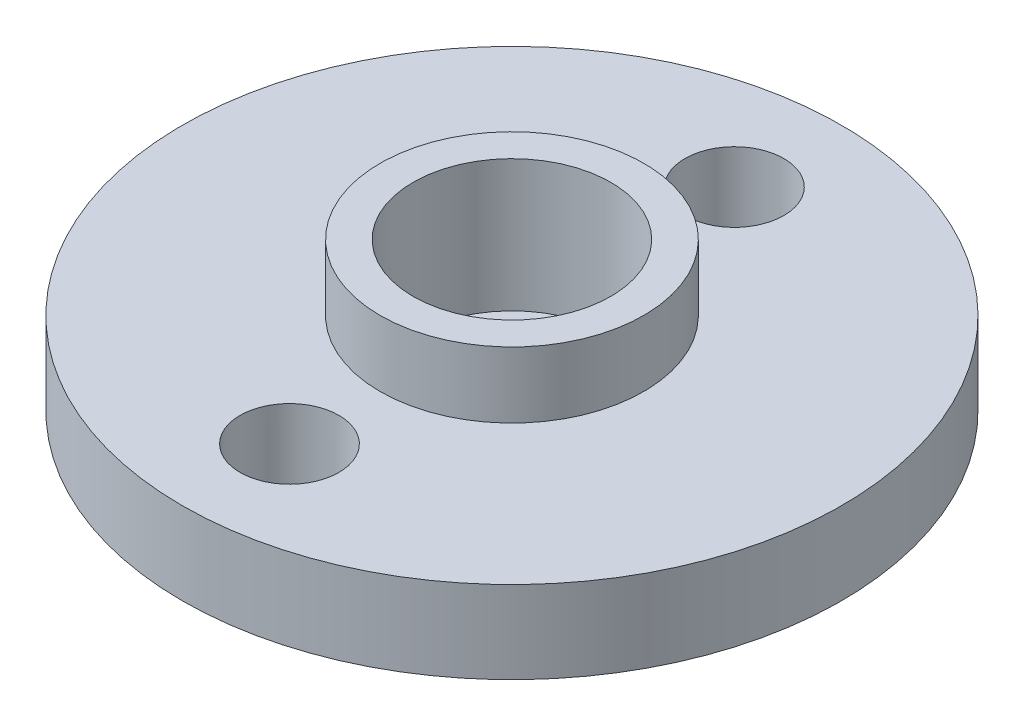
SolidWorks part; units mm, degrees
material "Chrome Stainless Steel"
ref_plane "Front Plane" through (0, 0, 0) normal (0, 0, 1) x (1, 0, 0)
ref_plane "Top Plane" through (0, 0, 0) normal (0, 1, 0) x (1, 0, 0)
ref_plane "Right Plane" through (0, 0, 0) normal (1, 0, 0) x (0, 0, -1)
sketch "Sketch1" plane through (0, 0, 0) normal (0, 0, 1) x (1, 0, 0)
  line L0 (0, 3.4245) -> (0, 0) construction
  line L1 (3, 0) -> (4, 0)
  line L2 (4, 0) -> (4, -2)
  line L3 (4, -2) -> (10, -2)
  line L4 (10, -2) -> (10, -4.5)
  line L5 (10, -4.5) -> (1.5, -4.5)
  line L6 (0, -4.5) -> (0, 0) construction
  line L7 (3, 0) -> (3, -4)
  line L8 (3, -4) -> (1.5, -4)
  line L9 (1.5, -4) -> (1.5, -4.5)
  line L10 (1.5, -4.5) -> (0, -4.5) construction
  line L11 (0, 0) -> (0, -4.5) construction
  line L12 (0, -4.5) -> (0, -6.9835) construction
  line L13 (0, 0) -> (3, 0) construction
  dimension "D1" = 10
  dimension "D2" = 4
  dimension "D3" = 3
  dimension "D4" = 2
  dimension "D5" = 2.5
  dimension "D6" = 0.5
  dimension "D7" = 1.5
revolve "Revolve1" add sketch "Sketch1" angle 360 about L0
sketch "Sketch2" plane through (0, -4.5, 0) normal (0, -1, 0) x (1, 0, 0)
  line L0 (0, 0) -> (0, -11.3657) construction
  line L1 (-7.8096, 0) -> (7.8096, 0) construction
  circle A0 centre (0, -7.5) radius 1.5
  circle A1 centre (-7.5, 0) radius 1.5
  circle A2 centre (0, 7.5) radius 1.5
  circle A3 centre (7.5, 0) radius 1.5
  point P14 (0, 0)
  point P15 (0, 0)
  dimension "D1" = 3
  dimension "D2" = 7.5
  dimension "D3" = 4
sketch "Sketch3" plane through (0, -2, 0) normal (0, 1, 0) x (1, 0, 0)
  line L0 (0, 0) -> (0, 6.75)
sketch "Sketch4" plane through (0, -2, 0) normal (0, 1, 0) x (1, 0, 0)
  circle A0 centre (0, 6.75) radius 1.5
extrude "Cut-Extrude1" cut sketch "Sketch4" against normal through all
pattern_circular "CirPattern1" count 4 over 360 about axis through (-7.8096, -4.5, 0) along (1, 0, 0) of "Cut-Extrude1"
